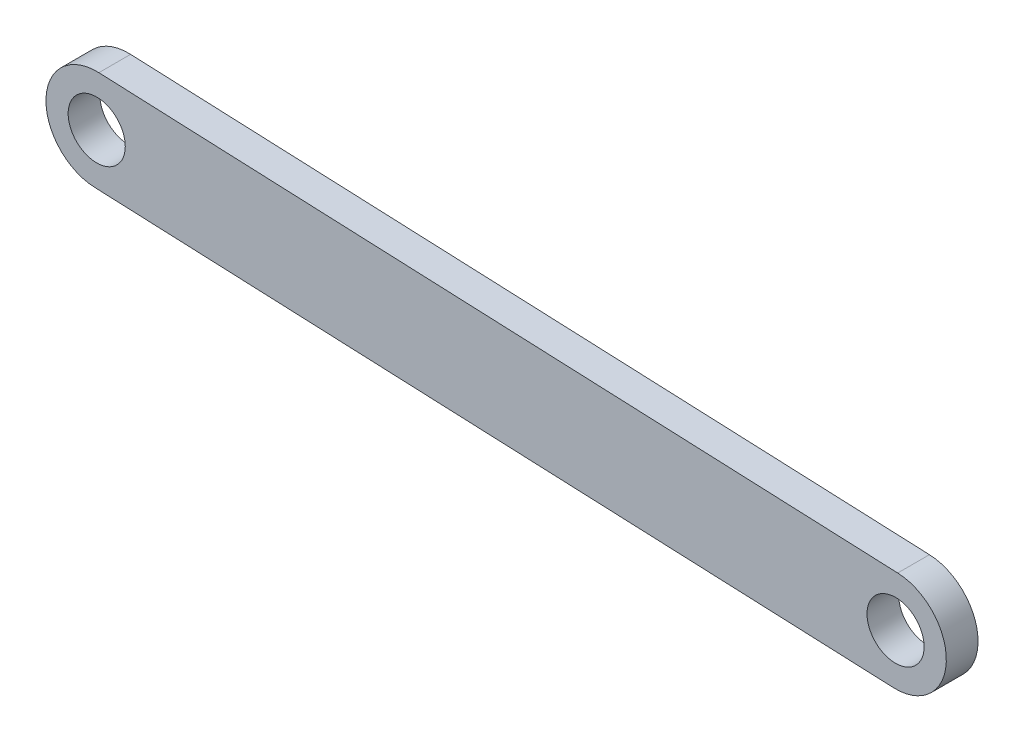
SolidWorks part; units mm, degrees
ref_plane "前视基准面" through (0, 0, 0) normal (0, 0, 1) x (1, 0, 0)
ref_plane "上视基准面" through (0, 0, 0) normal (0, 1, 0) x (1, 0, 0)
ref_plane "右视基准面" through (0, 0, 0) normal (1, 0, 0) x (0, 0, -1)
sketch "草图1" plane through (0, 0, 0) normal (0, 0, 1) x (1, 0, 0)
  line L0 (150.978, 33.8432) -> (276.8647, 28.5029) construction
  line L1 (151.317, 41.8361) -> (277.2038, 36.4957)
  line L2 (150.6389, 25.8504) -> (276.5257, 20.5101)
  arc A0 (151.317, 41.8361) -> (150.6389, 25.8504) centre (150.978, 33.8432) ccw
  arc A1 (276.5257, 20.5101) -> (277.2038, 36.4957) centre (276.8647, 28.5029) ccw
  circle A2 centre (150.978, 33.8432) radius 4.5
  circle A3 centre (276.8647, 28.5029) radius 4.5
  point P3 (213.9214, 31.1731)
  dimension "D1" = 9
  dimension "D2" = 9
  dimension "D3" = 8
  dimension "D4" = 126
extrude "凸台-拉伸1" add sketch "草图1" along normal blind 5
